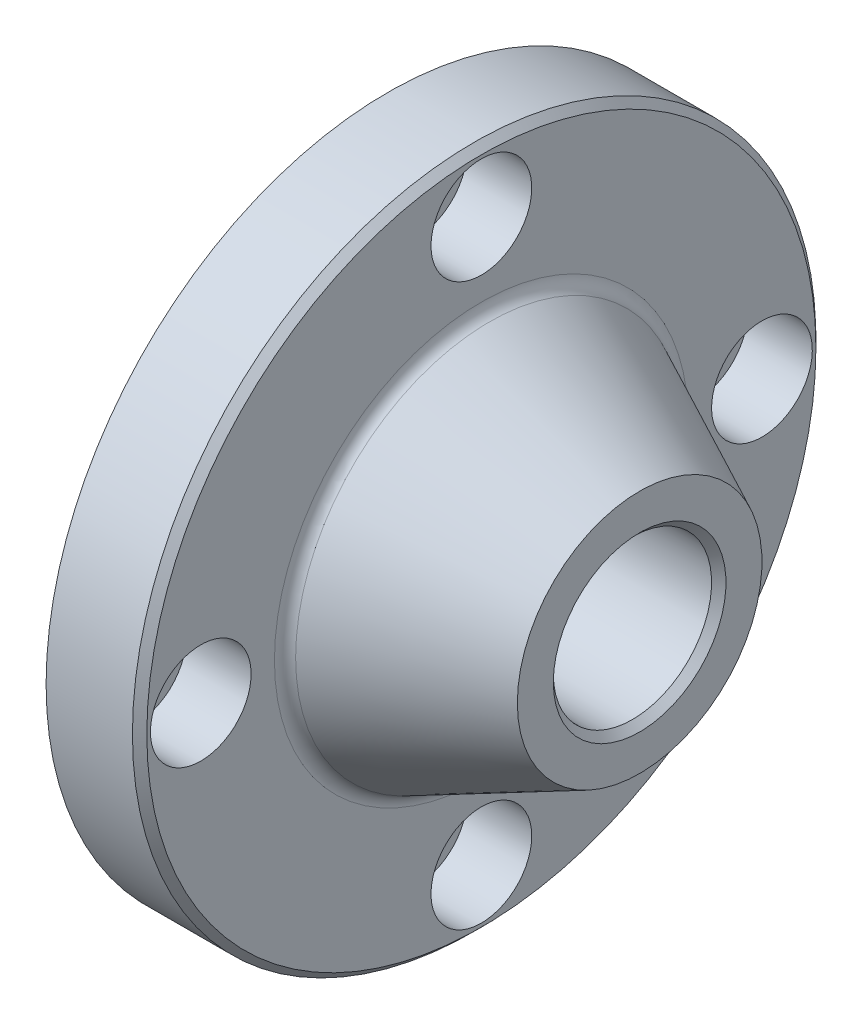
SolidWorks part; units mm, degrees
ref_plane "前视基准面" through (0, 0, 0) normal (0, 0, 1) x (1, 0, 0)
ref_plane "上视基准面" through (0, 0, 0) normal (0, 1, 0) x (1, 0, 0)
ref_plane "右视基准面" through (0, 0, 0) normal (1, 0, 0) x (0, 0, -1)
sketch "草图1" plane through (0, 0, 0) normal (0, 0, 1) x (1, 0, 0)
  line L0 (0, 0) -> (45, 0) construction
  line L1 (45, 11) -> (45, 17)
  line L2 (45, 17) -> (23, 27.5)
  line L3 (23, 27.5) -> (23, 47.5)
  line L4 (23, 47.5) -> (10, 47.5)
  line L5 (10, 47.5) -> (10, 31)
  line L6 (10, 31) -> (0, 31)
  line L7 (0, 31) -> (0, 22.5)
  line L8 (0, 22.5) -> (15, 22.5)
  line L9 (15, 22.5) -> (15, 11)
  line L10 (15, 11) -> (45, 11)
  point P12 (45, 14)
  dimension "D1" = 11
  dimension "D2" = 17
  dimension "D3" = 27.5
  dimension "D4" = 10
  dimension "D5" = 15
  dimension "D6" = 31
  dimension "D7" = 22.5
  dimension "D8" = 45
  dimension "D9" = 13
  dimension "D10" = 47.5
revolve "旋转1" add sketch "草图1" angle 360 about L0
chamfer "倒角1" distance 1 angle 45 1 edges at (45, 0, 11)
chamfer "倒角2" distance 1 angle 45 1 edges at (0, 0, 31)
chamfer "倒角3" distance 1 angle 45 1 edges at (23, 0, 47.5)
fillet "圆角1" radius 2 1 edges at (23, 0, 27.5)
sketch "草图2" plane through (23, 0, 0) normal (1, 0, 0) x (0, 0, -1)
  circle A0 centre (0, 0) radius 39 construction
  circle A1 centre (0, 39) radius 4.5
  dimension "D1" = 78
  dimension "D2" = 9
extrude "切除-拉伸1" cut sketch "草图2" against normal through all
sketch "草图3" plane through (10, 0, 0) normal (-1, 0, 0) x (0, 0, 1)
  circle A1 centre (0, 39) radius 7
  dimension "D1" = 14
extrude "切除-拉伸2" cut sketch "草图3" along normal blind 9 from surface at -13 starting at face at (23, 39, -4.5)
pattern_circular "阵列(圆周)2" count 4 over 360 about axis through (0, 0, 0) along (1, 0, 0) of "切除-拉伸1", "切除-拉伸2"
